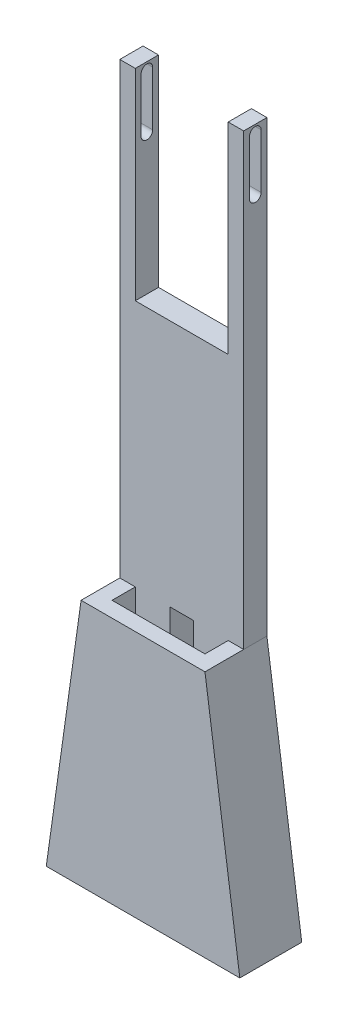
SolidWorks part; units mm, degrees
ref_plane "前视基准面" through (0, 0, 0) normal (0, 0, 1) x (1, 0, 0)
ref_plane "上视基准面" through (0, 0, 0) normal (0, 1, 0) x (1, 0, 0)
ref_plane "右视基准面" through (0, 0, 0) normal (1, 0, 0) x (0, 0, -1)
other "Configuration Table"
sketch "草图1" plane through (0, 0, 0) normal (0, 0, 1) x (1, 0, 0)
  line L0 (-550.3356, 530.4087) -> (-550.3356, -369.5913)
  line L1 (-550.3356, -369.5913) -> (-390.3356, -369.5913)
  line L2 (-390.3356, -369.5913) -> (-390.3356, 530.4087)
  line L4 (-410.3356, 450.4087) -> (-410.3356, 530.4087)
  line L5 (-530.3356, 530.4087) -> (-530.3356, 450.4087)
  line L6 (-530.3356, 530.4087) -> (-550.3356, 530.4087)
  line L7 (-390.3356, 530.4087) -> (-410.3356, 530.4087)
  arc A1 (-410.3356, 450.4087) -> (-530.3356, 450.4087) centre (-470.3356, 450.4087) cw
  dimension "D3" = 60
  dimension "D4" = 80
  dimension "D1" = 900
  dimension "D2" = 160
  dimension "D5" = 80
extrude "凸台-拉伸1" add sketch "草图1" along normal blind 30
sketch "草图5" plane through (0, 0, 30) normal (0, 0, 1) x (1, 0, 0)
  line L0 (-550.3356, -369.5913) -> (-550.3356, -49.5913)
  line L1 (-550.3356, 530.4087) -> (-550.3356, -369.5913) construction
  line L2 (-550.3356, -49.5913) -> (-390.3356, -49.5913)
  line L3 (-390.3356, -369.5913) -> (-390.3356, 530.4087) construction
  line L4 (-390.3356, -49.5913) -> (-390.3356, -369.5913)
  line L5 (-390.3356, -369.5913) -> (-550.3356, -369.5913)
  dimension "D1" = 320
extrude "凸台-拉伸4" add sketch "草图5" along normal blind 50
sketch "草图6" plane through (0, 0, 30) normal (0, 0, 1) x (1, 0, 0)
  line L0 (-530.3356, -49.5913) -> (-530.3356, -349.5913)
  line L1 (-390.3356, -49.5913) -> (-550.3356, -49.5913) construction
  line L2 (-530.3356, -349.5913) -> (-410.3356, -349.5913)
  line L3 (-410.3356, -349.5913) -> (-410.3356, -49.5913)
  line L4 (-390.3356, -49.5913) -> (-550.3356, -49.5913) construction
  line L5 (-410.3356, -49.5913) -> (-530.3356, -49.5913)
  line L6 (-550.3356, -49.5913) -> (-550.3356, -369.5913) construction
  line L7 (-390.3356, -369.5913) -> (-390.3356, -49.5913) construction
  line L8 (-550.3356, -369.5913) -> (-390.3356, -369.5913) construction
  dimension "D1" = 20
  dimension "D2" = 20
  dimension "D3" = 20
extrude "切除-拉伸1" cut sketch "草图6" along normal blind 30
sketch "草图7" plane through (0, 0, 30) normal (0, 0, 1) x (1, 0, 0)
  line L0 (-485.3356, -49.5913) -> (-485.3356, -329.5913)
  line L1 (-485.3356, -329.5913) -> (-455.3356, -329.5913)
  line L2 (-455.3356, -329.5913) -> (-455.3356, -49.5913)
  line L3 (-455.3356, -49.5913) -> (-485.3356, -49.5913)
  line L4 (-390.3356, -369.5913) -> (-390.3356, -49.5913) construction
  line L5 (-550.3356, -369.5913) -> (-390.3356, -369.5913) construction
  dimension "D1" = 30
  dimension "D2" = 65
  dimension "D3" = 280
  dimension "D4" = 40
extrude "切除-拉伸2" cut sketch "草图7" against normal through all
sketch "草图9" plane through (-530.3356, 0, 0) normal (1, 0, 0) x (0, 0, -1)
  line L0 (-30, 450.4087) -> (0, 450.4087) construction
  line L1 (-7.5, 450.4087) -> (-7.5, 520.4087)
  line L2 (-22.5, 520.4087) -> (-22.5, 450.4087)
  arc A0 (-7.5, 450.4087) -> (-22.5, 450.4087) centre (-15, 450.4087) cw
  arc A1 (-7.5, 520.4087) -> (-22.5, 520.4087) centre (-15, 520.4087) ccw
  dimension "D1" = 7.5
  dimension "D2" = 70
extrude "切除-拉伸4" cut sketch "草图9" against normal through all both and the other way through all
ref_plane "基准面2" through (-470.3356, 0, 0) normal (1, 0, 0) x (0, 0, -1)
sketch "草图10" plane through (0, 0, 30) normal (0, 0, 1) x (1, 0, 0)
  line L0 (-530.3356, 450.4087) -> (-530.3356, 270.4087)
  line L1 (-530.3356, 270.4087) -> (-410.3356, 270.4087)
  line L2 (-410.3356, 270.4087) -> (-410.3356, 450.4087)
  line L3 (-530.3356, 450.4087) -> (-410.3356, 450.4087)
  dimension "D1" = 180
extrude "切除-拉伸5" cut sketch "草图10" against normal through all contours L3 L2 L1 L0
sketch "草图11" plane through (0, 0, 80) normal (0, 0, 1) x (1, 0, 0)
  line L0 (-550.3356, -369.5913) -> (-595.3356, -369.5913)
  line L1 (-390.3356, -369.5913) -> (-345.3356, -369.5913)
  line L2 (-595.3356, -369.5913) -> (-550.3356, -49.5913)
  line L3 (-345.3356, -369.5913) -> (-390.3356, -49.5913)
  line L4 (-550.3356, -369.5913) -> (-550.3356, -49.5913)
  line L5 (-390.3356, -49.5913) -> (-390.3356, -369.5913)
extrude "凸台-拉伸5" add sketch "草图11" against normal blind 80
